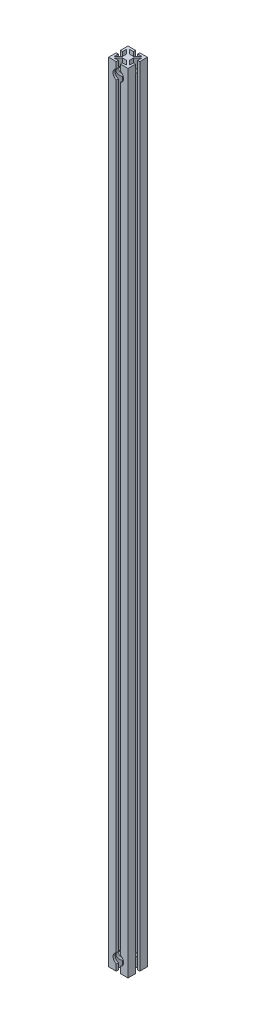
SolidWorks part; units mm, degrees
ref_plane "Front Plane" through (0, 0, 0) normal (0, 0, 1) x (1, 0, 0)
ref_plane "Top Plane" through (0, 0, 0) normal (0, 1, 0) x (1, 0, 0)
ref_plane "Right Plane" through (0, 0, 0) normal (1, 0, 0) x (0, 0, -1)
sketch "Sketch2" plane through (0.5947, 0, 0.5947) normal (0, 1, 0) x (1, 0, 0)
  line L0 (-0.5947, 0.5947) -> (-0.5947, 20.2394) construction
  line L1 (-0.5947, 0.5947) -> (-20.2394, 0.5947) construction
  line L2 (-0.5947, 0.5947) -> (-20.2394, 20.2394) construction
  line L3 (-19.6447, 19.6447) -> (-4.6587, 19.6447)
  line L4 (-4.6587, 19.6447) -> (-4.6587, 15.5807)
  line L5 (-4.6587, 15.5807) -> (-12.707, 15.5807)
  line L6 (-12.707, 15.5807) -> (-4.4774, 7.3511)
  line L7 (-4.4774, 7.3511) -> (3.288, 7.3511)
  line L8 (-19.6447, 19.6447) -> (-19.6447, 4.6587)
  line L9 (-19.6447, 4.6587) -> (-15.5807, 4.6587)
  line L10 (-15.5807, 4.6587) -> (-15.5807, 12.707)
  line L11 (-15.5807, 12.707) -> (-7.3511, 4.4774)
  line L12 (-7.3511, 4.4774) -> (-7.3511, -3.288)
  line L13 (-4.4774, -6.1617) -> (3.288, -6.1617)
  line L14 (-12.707, -14.3913) -> (-4.4774, -6.1617)
  line L15 (-4.6587, -14.3913) -> (-12.707, -14.3913)
  line L16 (-4.6587, -18.4553) -> (-4.6587, -14.3913)
  line L17 (-19.6447, -18.4553) -> (-4.6587, -18.4553)
  line L18 (-19.6447, -18.4553) -> (-19.6447, -3.4693)
  line L19 (-19.6447, -3.4693) -> (-15.5807, -3.4693)
  line L20 (-15.5807, -3.4693) -> (-15.5807, -11.5176)
  line L21 (-15.5807, -11.5176) -> (-7.3511, -3.288)
  line L22 (11.5176, 15.5807) -> (3.288, 7.3511)
  line L23 (3.4693, 15.5807) -> (11.5176, 15.5807)
  line L24 (3.4693, 19.6447) -> (3.4693, 15.5807)
  line L25 (18.4553, 19.6447) -> (3.4693, 19.6447)
  line L26 (18.4553, 19.6447) -> (18.4553, 4.6587)
  line L27 (18.4553, 4.6587) -> (14.3913, 4.6587)
  line L28 (14.3913, 4.6587) -> (14.3913, 12.707)
  line L29 (14.3913, 12.707) -> (6.1617, 4.4774)
  line L30 (6.1617, 4.4774) -> (6.1617, -3.288)
  line L31 (14.3913, -11.5176) -> (6.1617, -3.288)
  line L32 (14.3913, -3.4693) -> (14.3913, -11.5176)
  line L33 (18.4553, -3.4693) -> (14.3913, -3.4693)
  line L34 (18.4553, -18.4553) -> (18.4553, -3.4693)
  line L35 (18.4553, -18.4553) -> (3.4693, -18.4553)
  line L36 (3.4693, -18.4553) -> (3.4693, -14.3913)
  line L37 (3.4693, -14.3913) -> (11.5176, -14.3913)
  line L38 (11.5176, -14.3913) -> (3.288, -6.1617)
  point P26 (-7.3511, 0.5947)
  point P27 (-0.5947, 7.3511)
  point P44 (-0.5947, -6.1617)
  dimension "D1" = 38.1
  dimension "D2" = 8.128
  dimension "D3" = 13.5128
  dimension "D4" = 4.064
  dimension "D5" = 4.064
extrude "Boss-Extrude1" add sketch "Sketch2" along normal up to surface (1546.225 mm away)
other "1515<1>"
ref_plane "midplane" through (0, 773.1125, 0) normal (0, 1, 0) x (-1, 0, 0)
sketch "Sketch3" plane through (0, 0, 19.05) normal (0, 0, 1) x (1, 0, 0)
  line L0 (4.064, 0) -> (19.05, 0) construction
  circle A0 centre (0, 21.844) radius 10.287
  dimension "D1" = 20.574
  dimension "D2" = 21.844
extrude "Cut-Extrude1" cut sketch "Sketch3" against normal blind 16.51
mirror "Mirror1" about plane through (0, 0, 0) normal (0, 0, 1) of "Cut-Extrude1"
mirror "Mirror2" about plane through (0, 773.1125, 0) normal (0, 1, 0) of "Mirror1", "Cut-Extrude1"
